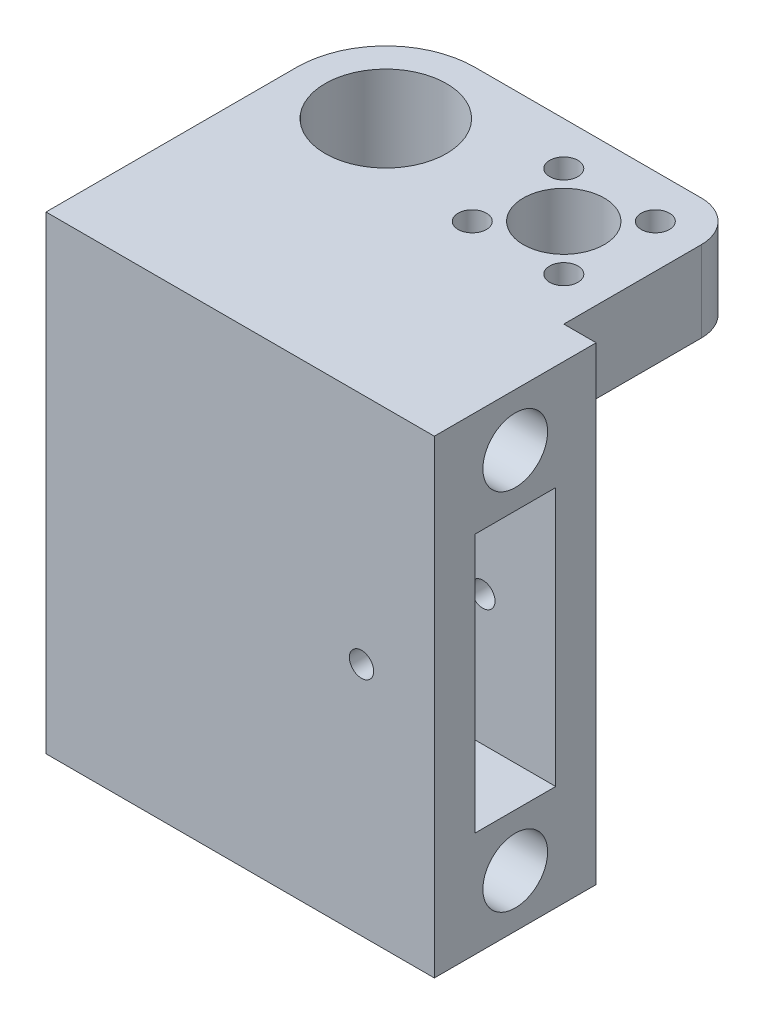
SolidWorks part; units mm, degrees
ref_plane "前视基准面" through (0, 0, 0) normal (0, 0, 1) x (1, 0, 0)
ref_plane "上视基准面" through (0, 0, 0) normal (0, 1, 0) x (1, 0, 0)
ref_plane "右视基准面" through (0, 0, 0) normal (1, 0, 0) x (0, 0, -1)
sketch "草图1" plane through (0, 0, 0) normal (0, 1, 0) x (1, 0, 0)
  line L0 (-11, 0) -> (-11, -11)
  line L1 (-11, -11) -> (11, -11)
  line L2 (11, -11) -> (11, 0)
  arc A0 (11, 0) -> (-11, 0) centre (0, 0) ccw
  circle A1 centre (0, 0) radius 7.5
  dimension "D1" = 22
extrude "凸台-拉伸1" add sketch "草图1" along normal blind 50
sketch "草图2" plane through (0, 50, 0) normal (0, 1, 0) x (1, 0, 0)
  line L0 (-11, 11) -> (0, 11)
  line L1 (-11, -11) -> (-33, -11)
  line L2 (-11, 11) -> (-28, 11)
  line L3 (-33, -11) -> (-33, 6)
  line L4 (-11, 0) -> (-11, -11)
  line L6 (-11, 0) -> (-11, -11) construction
  line L7 (-11, -11) -> (11, -11) construction
  arc A0 (-33, 6) -> (-28, 11) centre (-28, 6) cw
  arc A1 (0, 11) -> (-11, 0) centre (0, 0) ccw
  arc A2 (11, 0) -> (-11, 0) centre (0, 0) ccw construction
  dimension "D1" = 5
extrude "凸台-拉伸2" add sketch "草图2" against normal blind 10
sketch "草图3" plane through (0, 50, 0) normal (0, 1, 0) x (1, 0, 0)
  line L0 (-31.5355, 9.5355) -> (-11, -11) construction
  line L1 (-33, -11) -> (11, -11) construction
  line L2 (-33, -11) -> (-11, 11) construction
  line L3 (0, 11) -> (-28, 11) construction
  arc A0 (-28, 11) -> (-33, 6) centre (-28, 6) ccw construction
  circle A1 centre (-22, 0) radius 8 construction
  circle A2 centre (-22, 0) radius 5
  circle A3 centre (-27.6569, 5.6569) radius 1.75
  circle A4 centre (-16.3431, 5.6569) radius 1.75
  circle A5 centre (-16.3431, -5.6569) radius 1.75
  circle A6 centre (-27.6569, -5.6569) radius 1.75
  point P12 (-22, 0)
  point P27 (-22, 0)
  dimension "D1" = 16
  dimension "D2" = 10
  dimension "D3" = 3.5
  dimension "D4" = 4
extrude "切除-拉伸1" cut sketch "草图3" against normal blind 10
mirror "镜向1" about plane through (11, 50, 11) normal (-1, 0, 0) of bodies 108
sketch "草图4" plane through (0, 0, 0) normal (0, -1, 0) x (1, 0, 0)
  line L1 (-33, 11) -> (11, 11)
  line L2 (-33, 11) -> (-33, -11)
  line L3 (-33, -11) -> (11, -11)
  line L4 (11, 11) -> (11, -11)
  dimension "D1" = 22
extrude "切除-拉伸2" cut sketch "草图4" against normal blind 50
sketch "草图5" plane through (0, 0, 11) normal (0, 0, 1) x (1, 0, 0)
  line L1 (11, 50) -> (59, 50)
  line L2 (11, 50) -> (11, -8)
  line L3 (11, -8) -> (59, -8)
  line L4 (59, 50) -> (59, -8)
  dimension "D1" = 58
  dimension "D2" = 48
extrude "凸台-拉伸3" add sketch "草图5" along normal blind 20
sketch "草图6" plane through (59, 0, 0) normal (1, 0, 0) x (0, 0, -1)
  line L0 (-31, 50) -> (-11, 50) construction
  line L3 (-31, -8) -> (-31, 50) construction
  circle A0 centre (-21, 43.5) radius 4
  circle A1 centre (-21, -1.5) radius 4
  dimension "D1" = 8
  dimension "D3" = 8
  dimension "D4" = 45
  dimension "D2" = 6.5
  dimension "10" = 10
extrude "切除-拉伸3" cut sketch "草图6" against normal blind 50
sketch "草图7" plane through (59, 0, 0) normal (1, 0, 0) x (0, 0, -1)
  line L0 (-21, 50) -> (-21, -8) construction
  line L1 (-31, 50) -> (-11, 50) construction
  line L2 (-31, -8) -> (-11, -8) construction
  line L3 (-31, 21) -> (-11, 21) construction
  line L4 (-31, -8) -> (-31, 50) construction
  line L5 (-11, -8) -> (-11, 50) construction
  line L18 (-26, 5) -> (-16, 5)
  line L19 (-26, 5) -> (-26, 37)
  line L20 (-26, 37) -> (-16, 37)
  line L21 (-16, 5) -> (-16, 37)
  line L22 (-26, 5) -> (-16, 37) construction
  line L23 (-26, 37) -> (-16, 5) construction
  point P12 (-21, 21)
  dimension "D1" = 10
  dimension "D2" = 32
extrude "切除-拉伸4" cut sketch "草图7" against normal blind 50
sketch "草图8" plane through (0, 0, 11) normal (0, 0, -1) x (-1, 0, 0)
  line L0 (-59, 21.08) -> (-11, 21.08) construction
  line L3 (-11, -8) -> (-59, -8) construction
  line L4 (-59, -8) -> (-59, 50) construction
  circle A0 centre (-50, 21.08) radius 1.5
  dimension "D2" = 3
  dimension "D3" = 9
  dimension "D1" = 29.08
extrude "切除-拉伸5" cut sketch "草图8" against normal blind 20
